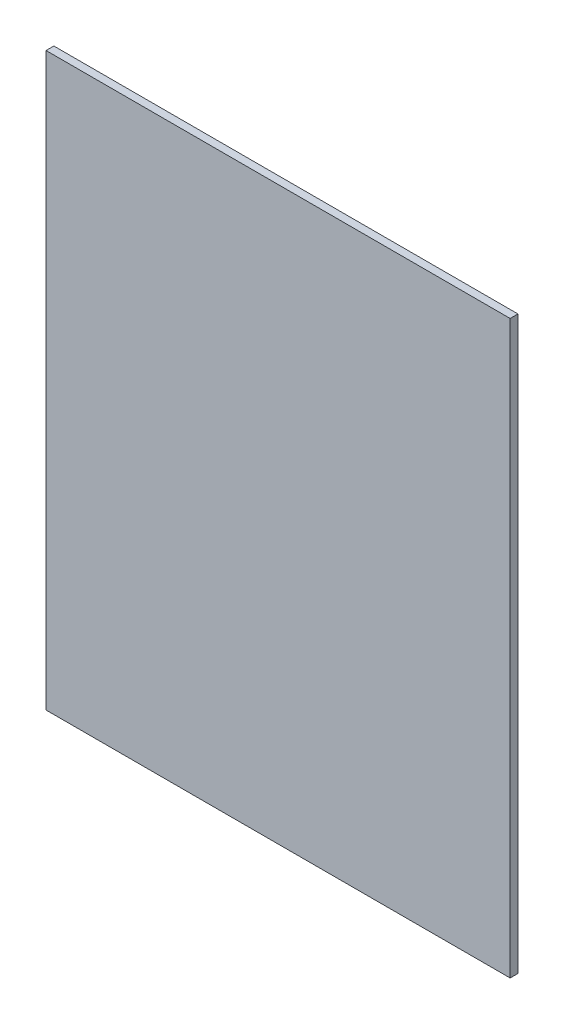
SolidWorks part; units mm, degrees
material "Maple"
ref_plane "Front Plane" through (0, 0, 0) normal (0, 0, 1) x (1, 0, 0)
ref_plane "Top Plane" through (0, 0, 0) normal (0, 1, 0) x (1, 0, 0)
ref_plane "Right Plane" through (0, 0, 0) normal (1, 0, 0) x (0, 0, -1)
sketch "Sketch1" plane through (0, 0, 0) normal (0, 0, 1) x (1, 0, 0)
  line L1 (0, 0) -> (660.4, 0)
  line L2 (0, 0) -> (0, 812.8)
  line L3 (0, 812.8) -> (660.4, 812.8)
  line L4 (660.4, 0) -> (660.4, 812.8)
  dimension "D1" = 660.4
  dimension "D2" = 812.8
extrude "Boss-Extrude1" add sketch "Sketch1" along normal blind 11.1125
